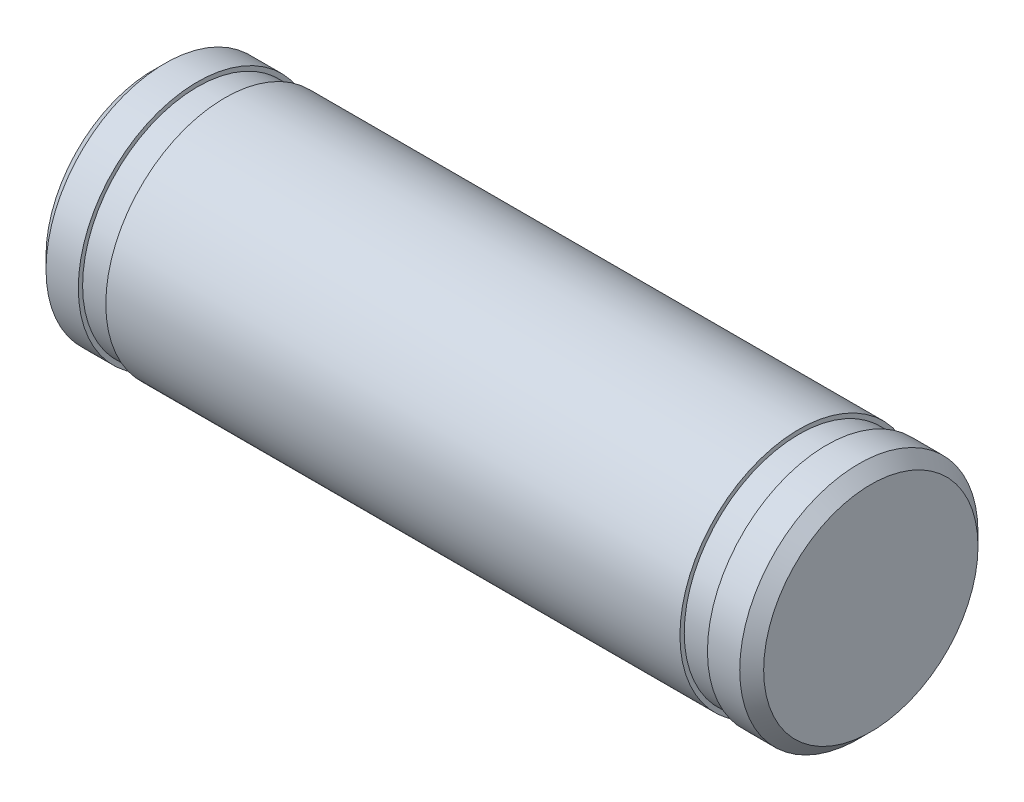
SolidWorks part; units mm, degrees
material "Chrome Stainless Steel"
ref_plane "Front Plane" through (0, 0, 0) normal (0, 0, 1) x (1, 0, 0)
ref_plane "Top Plane" through (0, 0, 0) normal (0, 1, 0) x (1, 0, 0)
ref_plane "Right Plane" through (0, 0, 0) normal (1, 0, 0) x (0, 0, -1)
sketch "Sketch1" plane through (0, 0, 0) normal (1, 0, 0) x (0, 0, -1)
  circle A0 centre (0, 0) radius 4.98
  dimension "D1" = 9.96
extrude "Boss-Extrude1" add sketch "Sketch1" along normal mid plane 30
sketch "Sketch2" plane through (-15, 0, 0) normal (-1, 0, 0) x (0, 0, 1)
  circle A0 centre (0, 0) radius 4.8
  circle A1 centre (0, 0) radius 4.98
  circle A2 centre (0, 0) radius 4.98
  dimension "D2" = 9.6
  dimension "D1" = 0
extrude "Cut-Extrude1" cut sketch "Sketch2" against normal blind 1.15 from offset 1.85 offset against normal yes
chamfer "Chamfer1" distance 0.5 angle 45 1 edges at (-15, 0, -4.98)
mirror "Mirror1" about plane through (0, 0, 0) normal (1, 0, 0) of "Cut-Extrude1"
chamfer "Chamfer2" distance 0.5 angle 45 1 edges at (15, 0, -4.98)
